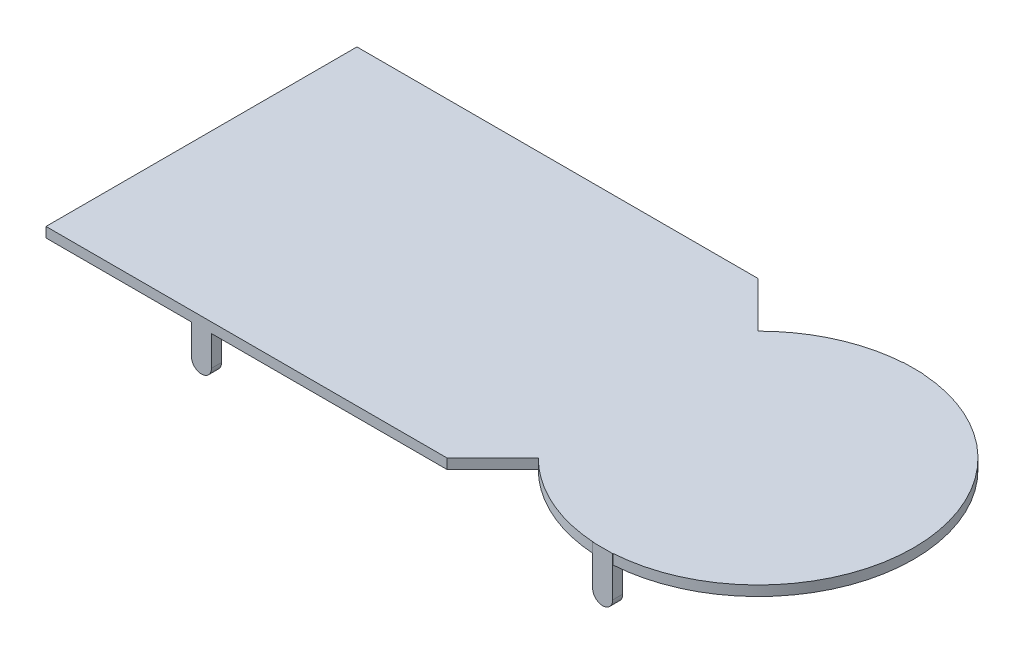
SolidWorks part; units mm, degrees
ref_plane "Front Plane" through (0, 0, 0) normal (0, 0, 1) x (1, 0, 0)
ref_plane "Top Plane" through (0, 0, 0) normal (0, 1, 0) x (1, 0, 0)
ref_plane "Right Plane" through (0, 0, 0) normal (1, 0, 0) x (0, 0, -1)
sketch "Sketch2" plane through (0, 0, 0) normal (0, 1, 0) x (1, 0, 0)
  line L0 (200, 155) -> (245.3984, 109.6016)
  line L1 (-200, -155) -> (200, -155)
  line L2 (-200, -155) -> (-200, 155)
  line L3 (-200, 155) -> (200, 155)
  line L5 (-200, -155) -> (200, 155) construction
  line L6 (-200, 155) -> (200, -155) construction
  line L7 (245.3984, -109.6016) -> (200, -155)
  arc A0 (245.3984, -109.6016) -> (245.3984, 109.6016) centre (355, 0) ccw
  point P0 (0, 0)
  dimension "D1" = 400
  dimension "D2" = 310
extrude "Boss-Extrude2" add sketch "Sketch2" along normal blind 10
sketch "Sketch6" plane through (0, 0, 155) normal (0, 0, 1) x (1, 0, 0)
  line L0 (-200, 10) -> (200, 10) construction
  line L1 (510, 10) -> (245.3984, 10) construction
  line L2 (-35, 10) -> (-55, 10)
  line L3 (-35, 10) -> (-35, -30)
  line L5 (-55, 10) -> (-55, -30)
  line L6 (365, 10) -> (345, 10)
  line L7 (365, 10) -> (365, -30)
  line L9 (345, 10) -> (345, -30)
  line L10 (-45, 10) -> (-45, -30) construction
  line L11 (-200, 10) -> (-200, 0) construction
  line L12 (355, 10) -> (355, -30) construction
  line L13 (510, 0) -> (510, 10) construction
  arc A0 (-55, -30) -> (-35, -30) centre (-45, -30) ccw
  arc A1 (345, -30) -> (365, -30) centre (355, -30) ccw
  dimension "D1" = 155
  dimension "D2" = 155
  dimension "D3" = 20
  dimension "D4" = 20
  dimension "D5" = 40
  dimension "D6" = 40
extrude "Boss-Extrude3" add sketch "Sketch6" against normal blind 310
sketch "Sketch7" plane through (-55, 0, 0) normal (-1, 0, 0) x (0, 0, 1)
  line L0 (-155, 0) -> (155, 0) construction
  line L1 (-145, -40) -> (145, -40)
  line L2 (-145, -40) -> (-145, 0)
  line L3 (-145, 0) -> (145, 0)
  line L4 (145, -40) -> (145, 0)
  line L5 (-145, -40) -> (145, 0) construction
  line L6 (-145, 0) -> (145, -40) construction
  line L7 (-155, 0) -> (-155, -30) construction
  line L8 (155, 0) -> (155, -30) construction
  line L9 (-155, -40) -> (155, -40) construction
  point P0 (0, -20)
  dimension "D1" = 10
  dimension "D2" = 10
  dimension "D3" = 0
extrude "Cut-Extrude1" cut sketch "Sketch7" against normal blind 589
